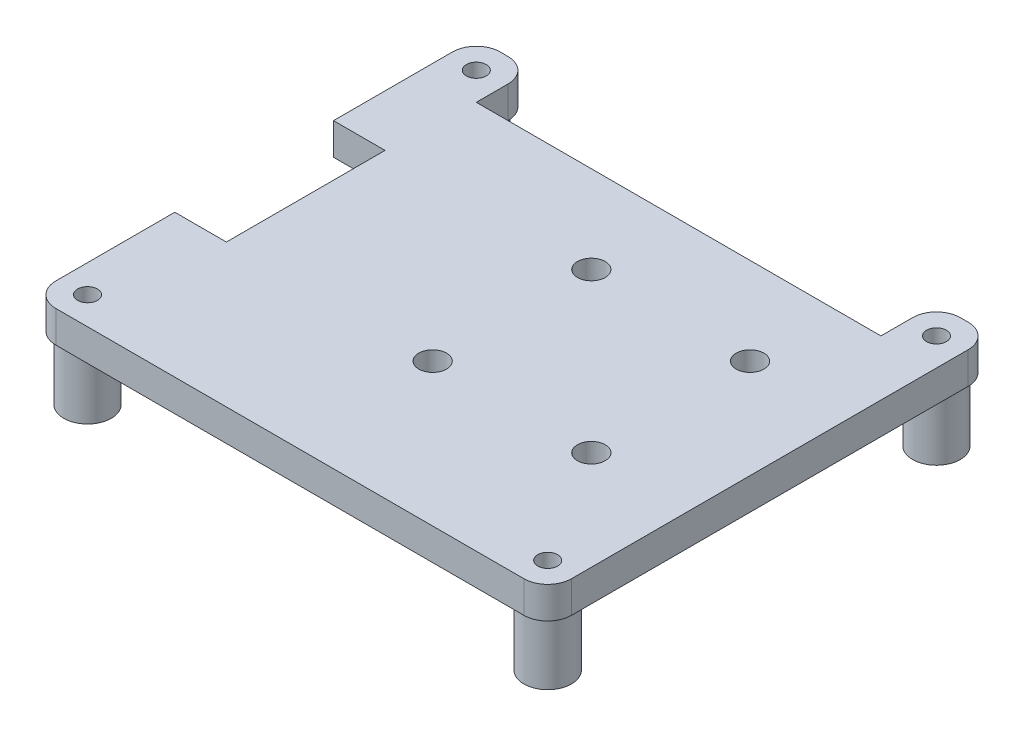
SolidWorks part; units mm, degrees
ref_plane "Front Plane" through (0, 0, 0) normal (0, 0, 1) x (1, 0, 0)
ref_plane "Top Plane" through (0, 0, 0) normal (0, 1, 0) x (1, 0, 0)
ref_plane "Right Plane" through (0, 0, 0) normal (1, 0, 0) x (0, 0, -1)
sketch "Sketch1" plane through (0, 0, 0) normal (0, 1, 0) x (1, 0, 0)
  line L0 (-29.1368, 14.2197) -> (-29.1368, 32.2197)
  line L1 (35.8632, -23.7803) -> (-29.1368, -23.7803)
  line L2 (35.8632, -23.7803) -> (35.8632, 32.2197)
  line L3 (35.8632, 32.2197) -> (28.8632, 32.2197)
  line L4 (-29.1368, -23.7803) -> (-29.1368, -5.7803)
  line L5 (-29.1368, 14.2197) -> (-22.6368, 14.2197)
  line L7 (-29.1368, -5.7803) -> (-22.6368, -5.7803)
  line L8 (-22.6368, 14.2197) -> (-22.6368, -5.7803)
  line L9 (-22.1368, 32.2197) -> (-29.1368, 32.2197)
  line L11 (-22.1368, 32.2197) -> (-22.1368, 25.2197)
  line L12 (-22.1368, 25.2197) -> (28.8632, 25.2197)
  line L13 (28.8632, 32.2197) -> (28.8632, 25.2197)
  circle A0 centre (32.3632, 28.7197) radius 1.25
  circle A1 centre (-25.6368, 28.7197) radius 1.25
  circle A2 centre (32.3632, -20.2803) radius 1.25
  circle A3 centre (-25.6368, -20.2803) radius 1.25
  point P0 (0, 0)
  point P14 (-29.1368, 4.2197)
  dimension "D11" = 2.5
  dimension "D12" = 2.5
  dimension "D13" = 2.5
  dimension "D14" = 2.5
  dimension "D2" = 56
  dimension "D3" = 3.5
  dimension "D4" = 3.5
  dimension "D5" = 3.5
  dimension "D6" = 3.5
  dimension "D7" = 3.5
  dimension "D8" = 3.5
  dimension "D9" = 3.5
  dimension "D10" = 3.5
  dimension "D15" = 3.5
  dimension "D16" = 20
  dimension "D17" = 7
  dimension "D18" = 3.5
  dimension "D19" = 58
  dimension "D20" = 18
extrude "Boss-Extrude1" add sketch "Sketch1" along normal blind 4
fillet "Fillet1" radius 3 6 edges at (28.8632, 2, -32.2197) (35.8632, 2, -32.2197) (35.8632, 2, 23.7803) (-29.1368, 2, 23.7803) (-22.1368, 2, -32.2197) (-29.1368, 2, -32.2197)
sketch "Sketch2" plane through (0, 4, 0) normal (0, 1, 0) x (1, 0, 0)
  line L1 (3.3632, 14.2197) -> (23.3632, 14.2197) construction
  line L2 (3.3632, 14.2197) -> (3.3632, -5.7803) construction
  line L3 (3.3632, -5.7803) -> (23.3632, -5.7803) construction
  line L4 (23.3632, 14.2197) -> (23.3632, -5.7803) construction
  line L6 (32.8632, 32.2197) -> (31.8632, 32.2197) construction
  line L8 (-29.1368, -5.7803) -> (-29.1368, -20.7803) construction
  circle A0 centre (23.3632, 14.2197) radius 1.75
  circle A1 centre (3.3632, 14.2197) radius 1.75
  circle A2 centre (3.3632, -5.7803) radius 1.75
  circle A3 centre (23.3632, -5.7803) radius 1.75
  point P6 (3.3632, 4.2197)
  point P9 (32.3632, 32.2197)
  dimension "D1" = 32.5
  dimension "D2" = 28
  dimension "D3" = 20
  dimension "D4" = 20
extrude "Cut-Extrude1" cut sketch "Sketch2" against normal blind 4
sketch "Sketch3" plane through (0, 0, 0) normal (0, -1, 0) x (1, 0, 0)
  circle A0 centre (-25.6368, 20.2803) radius 3
  circle A2 centre (-25.6368, -28.7197) radius 3
  circle A3 centre (32.3632, -28.7197) radius 3
  circle A4 centre (32.3632, 20.2803) radius 3
  circle A5 centre (-25.6368, 20.2803) radius 1.25
  circle A6 centre (32.3632, 20.2803) radius 1.25
  circle A8 centre (32.3632, -28.7197) radius 1.25
  circle A9 centre (-25.6368, -28.7197) radius 1.25
extrude "Boss-Extrude2" add sketch "Sketch3" along normal blind 8
